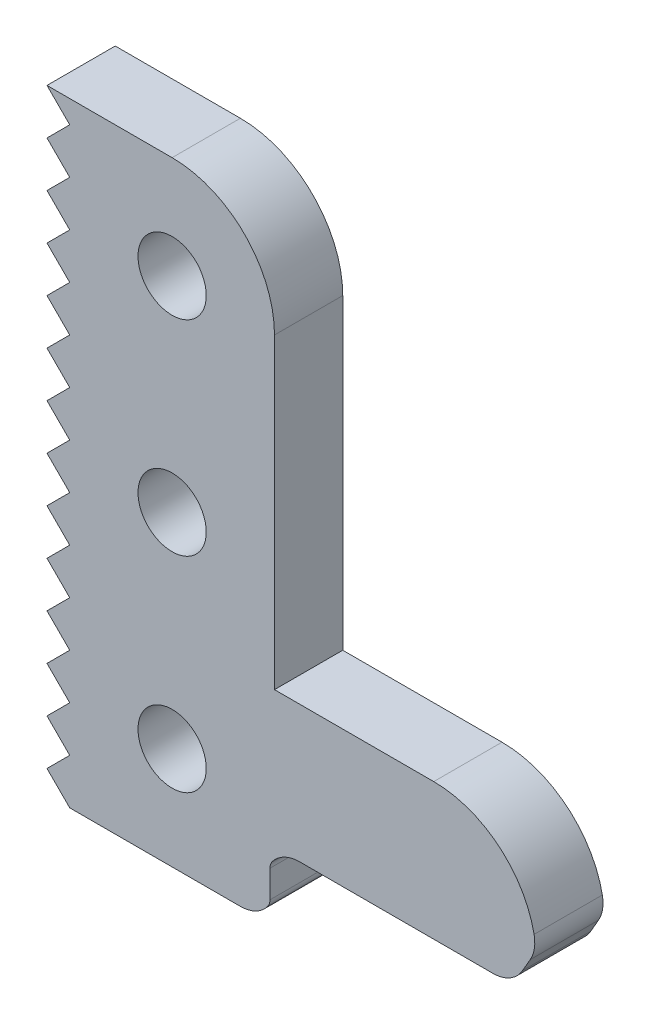
SolidWorks part; units mm, degrees
ref_plane "Alzado" through (0, 0, 0) normal (0, 0, 1) x (1, 0, 0)
ref_plane "Planta" through (0, 0, 0) normal (0, 1, 0) x (1, 0, 0)
ref_plane "Vista lateral" through (0, 0, 0) normal (1, 0, 0) x (0, 0, -1)
sketch "Model" plane through (0, 0, 0) normal (0, 0, 1) x (1, 0, 0)
  line L0 (10.4173, 265.129) -> (11.4173, 266.129)
  line L1 (11.4173, 266.129) -> (10.4173, 267.129)
  line L2 (10.4173, 267.129) -> (11.4173, 268.129)
  line L3 (11.4173, 268.129) -> (10.4173, 269.129)
  line L4 (10.4173, 269.129) -> (11.4173, 270.129)
  line L5 (11.4173, 270.129) -> (10.4173, 271.129)
  line L6 (10.4173, 271.129) -> (11.4173, 272.129)
  line L7 (11.4173, 272.129) -> (10.4173, 273.129)
  line L8 (10.4173, 273.129) -> (11.4173, 274.129)
  line L9 (11.4173, 274.129) -> (10.4173, 275.129)
  line L10 (10.4173, 275.129) -> (11.4173, 276.129)
  line L11 (11.4173, 276.129) -> (10.4173, 277.129)
  line L12 (10.4173, 277.129) -> (11.4173, 278.129)
  line L13 (11.4173, 278.129) -> (10.4173, 279.129)
  line L14 (10.4173, 279.129) -> (11.4173, 280.129)
  line L15 (11.4173, 280.129) -> (10.4173, 281.129)
  line L16 (10.4173, 281.129) -> (11.4173, 282.129)
  line L17 (11.4173, 282.129) -> (10.4173, 283.129)
  line L18 (10.4173, 283.129) -> (11.4173, 284.129)
  line L19 (11.4173, 284.129) -> (10.4173, 285.129)
  line L20 (10.4173, 285.129) -> (11.4173, 286.129)
  line L21 (11.4173, 286.129) -> (10.4173, 287.129)
  line L22 (10.4173, 287.129) -> (11.4173, 288.129)
  line L23 (11.4173, 288.129) -> (10.4173, 289.129)
  line L24 (10.4173, 289.129) -> (11.4173, 290.129)
  line L25 (11.4173, 290.129) -> (10.4173, 291.129)
  line L26 (11.4173, 264.129) -> (10.4173, 265.129)
  line L27 (15.9173, 291.129) -> (10.4173, 291.129)
  line L28 (20.4173, 273.129) -> (20.4173, 286.629)
  line L29 (11.4173, 264.129) -> (18.9173, 264.129)
  line L30 (20.4173, 273.129) -> (27.4173, 273.129)
  line L31 (21.5154, 267.129) -> (30.0154, 267.129)
  line L32 (31.3145, 267.879) -> (31.6571, 268.4725)
  line L33 (20.2164, 266.2303) -> (20.2164, 265.0278)
  circle A0 centre (15.9173, 268.629) radius 1.5
  circle A1 centre (15.9173, 277.629) radius 1.5
  arc A2 (20.4173, 286.629) -> (15.9173, 291.129) centre (15.9173, 286.629) ccw
  circle A3 centre (15.9173, 286.629) radius 1.5
  arc A4 (31.8284, 269.5192) -> (27.4173, 273.129) centre (27.4173, 268.629) ccw
  arc A5 (30.0154, 267.129) -> (31.3145, 267.879) centre (30.0154, 268.629) ccw
  arc A6 (18.9173, 264.129) -> (20.1159, 264.7271) centre (18.9173, 265.629) ccw
  arc A7 (21.5154, 267.129) -> (20.3169, 266.531) centre (21.5154, 265.629) ccw
  arc A8 (31.6571, 268.4725) -> (31.8284, 269.5192) centre (30.3581, 269.2225) ccw
  arc A9 (20.3169, 266.531) -> (20.2164, 266.2303) centre (20.7164, 266.2303) ccw
  arc A10 (20.1159, 264.7271) -> (20.2164, 265.0278) centre (19.7164, 265.0278) ccw
extrude "Saliente-Extruir1" add sketch "Model" along normal blind 3
